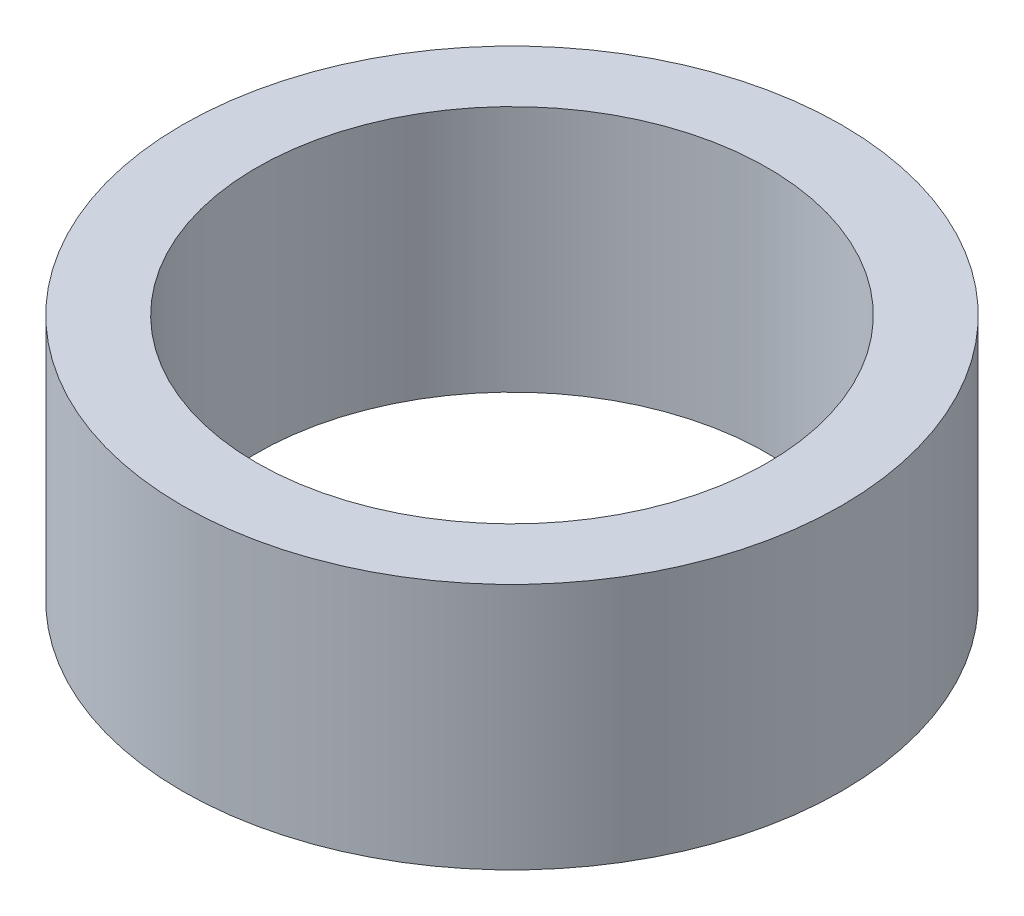
SolidWorks part; units mm, degrees
ref_plane "Front Plane" through (0, 0, 0) normal (0, 0, 1) x (1, 0, 0)
ref_plane "Top Plane" through (0, 0, 0) normal (0, 1, 0) x (1, 0, 0)
ref_plane "Right Plane" through (0, 0, 0) normal (1, 0, 0) x (0, 0, -1)
sketch "Sketch1" plane through (0, 0, 0) normal (0, 1, 0) x (1, 0, 0)
  circle A0 centre (0, 0) radius 4
  circle A1 centre (0, 0) radius 3.1
  dimension "D1" = 6.2
  dimension "D2" = 8
extrude "Boss-Extrude1" add sketch "Sketch1" along normal blind 3
